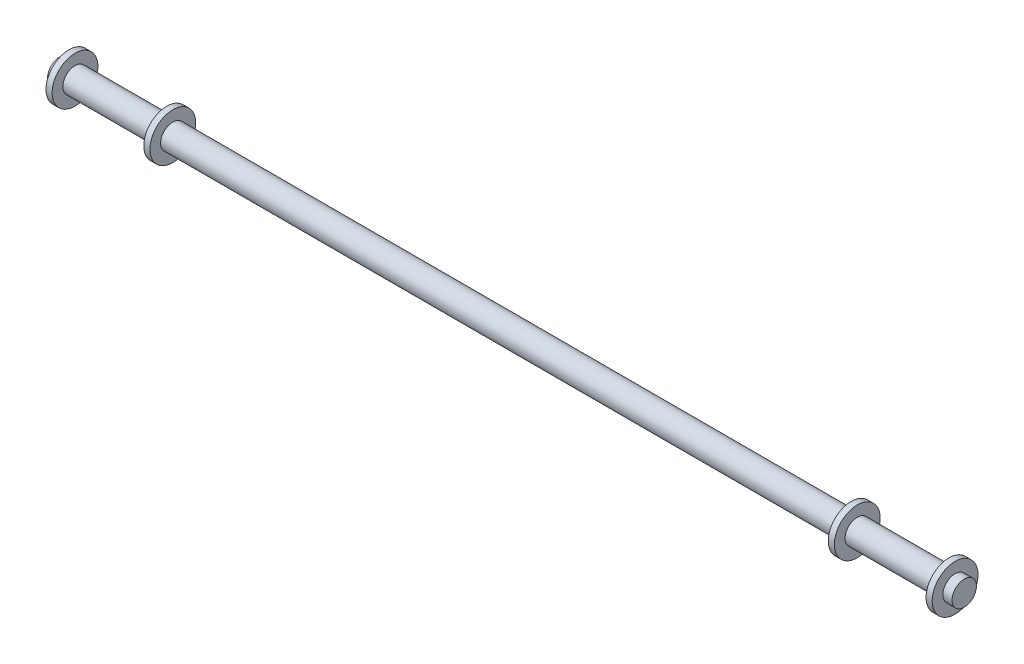
SolidWorks part; units mm, degrees
material "Plain Carbon Steel"
ref_plane "Front Plane" through (0, 0, 0) normal (0, 0, 1) x (1, 0, 0)
ref_plane "Top Plane" through (0, 0, 0) normal (0, 1, 0) x (1, 0, 0)
ref_plane "Right Plane" through (0, 0, 0) normal (1, 0, 0) x (0, 0, -1)
sketch "Sketch1" plane through (0, 0, 0) normal (1, 0, 0) x (0, 0, -1)
  circle A0 centre (0, 0) radius 10.16
  dimension "D1" = 20.32
extrude "Boss-Extrude1" add sketch "Sketch1" along normal mid plane 751.84
sketch "Sketch2" plane through (-375.92, 0, 0) normal (-1, 0, 0) x (0, 0, 1)
  circle A0 centre (0, 0) radius 19.05
  dimension "D1" = 38.1
extrude "Boss-Extrude2" add sketch "Sketch2" along normal blind 5.08 from offset 12.7 offset against normal yes
sketch "Sketch3" plane through (-375.92, 0, 0) normal (-1, 0, 0) x (0, 0, 1)
  circle A0 centre (0, 0) radius 19.05
  dimension "D1" = 38.1
extrude "Boss-Extrude3" add sketch "Sketch3" against normal blind 5.08 from offset 88.9 offset against normal yes
sketch "Sketch4" plane through (375.92, 0, 0) normal (1, 0, 0) x (0, 0, -1)
  circle A0 centre (0, 0) radius 19.05
  dimension "D1" = 38.1
extrude "Boss-Extrude4" add sketch "Sketch4" along normal blind 5.08 from offset 12.7 offset against normal yes
sketch "Sketch5" plane through (375.92, 0, 0) normal (1, 0, 0) x (0, 0, -1)
  circle A0 centre (0, 0) radius 19.05
  dimension "D1" = 38.1
extrude "Boss-Extrude5" add sketch "Sketch5" against normal blind 5.08 from offset 88.9
